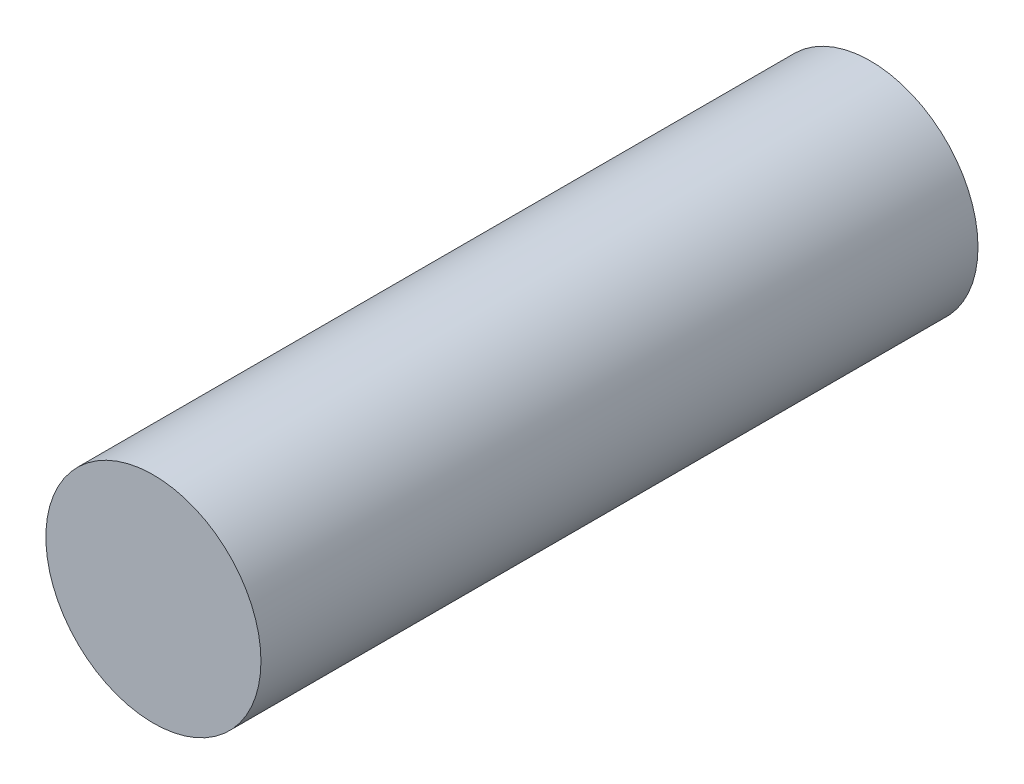
SolidWorks part; units mm, degrees
ref_plane "Front Plane" through (0, 0, 0) normal (0, 0, 1) x (1, 0, 0)
ref_plane "Top Plane" through (0, 0, 0) normal (0, 1, 0) x (1, 0, 0)
ref_plane "Right Plane" through (0, 0, 0) normal (1, 0, 0) x (0, 0, -1)
sketch "Sketch1" plane through (0, 0, 0) normal (0, 0, 1) x (1, 0, 0)
  circle A0 centre (0, 0) radius 15
  dimension "D1" = 30
extrude "Boss-Extrude1" add sketch "Sketch1" along normal blind 100
